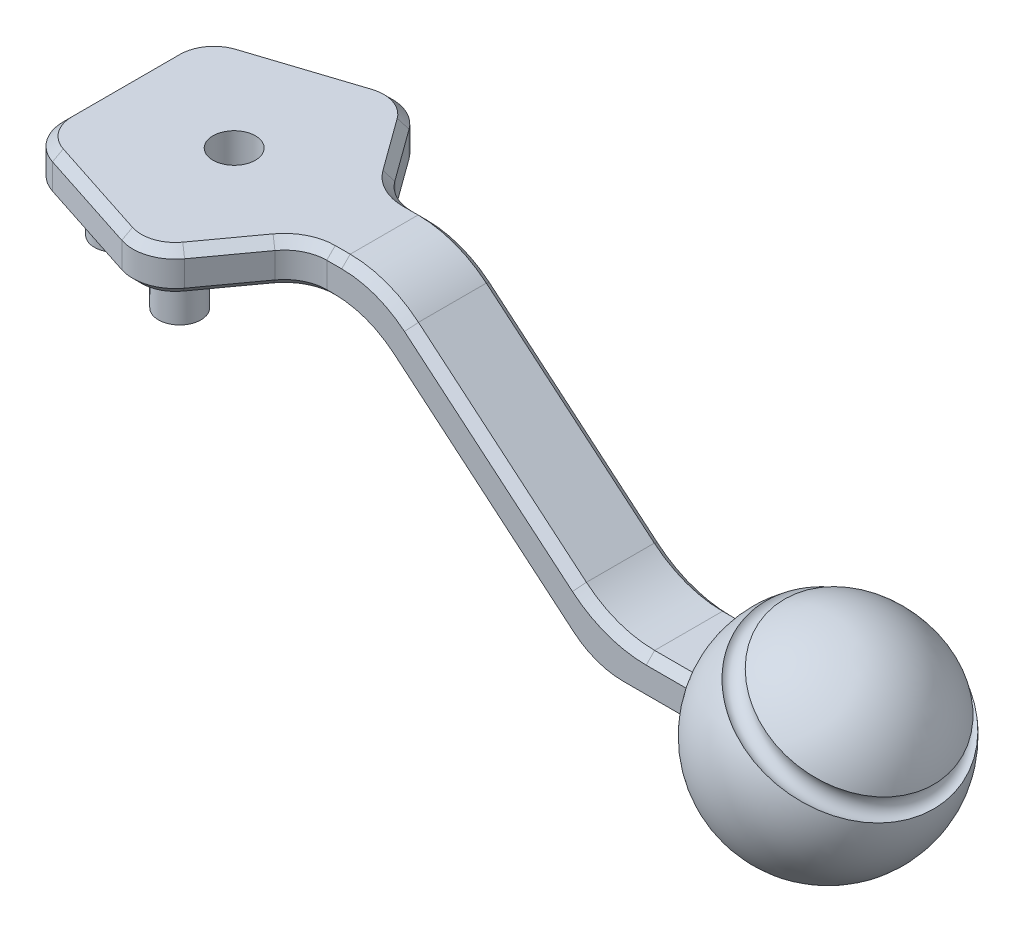
SolidWorks part; units mm, degrees
ref_plane "Front Plane" through (0, 0, 0) normal (0, 0, 1) x (1, 0, 0)
ref_plane "Top Plane" through (0, 0, 0) normal (0, 1, 0) x (1, 0, 0)
ref_plane "Right Plane" through (0, 0, 0) normal (1, 0, 0) x (0, 0, -1)
sketch "Sketch2" plane through (0, 0, 0) normal (0, 0, 1) x (1, 0, 0)
  line L0 (0, 31.75) -> (0, 0)
  line L1 (0, 0) -> (0, -31.75)
  arc A0 (0, -31.75) -> (0, 31.75) centre (0, 0) ccw
  dimension "D1" = 63.5
revolve "Revolve1" add sketch "Sketch2" angle 360 about L0
sketch "Sketch10" plane through (0, 0, 0) normal (1, 0, 0) x (0, 0, -1)
  line L1 (-12.7, 6.35) -> (12.7, 6.35)
  line L2 (-12.7, 6.35) -> (-12.7, -6.35)
  line L3 (-12.7, -6.35) -> (12.7, -6.35)
  line L4 (12.7, 6.35) -> (12.7, -6.35)
  line L5 (-12.7, 6.35) -> (12.7, -6.35) construction
  line L6 (-12.7, -6.35) -> (12.7, 6.35) construction
  point P0 (0, 0)
  dimension "D1" = 12.7
  dimension "D2" = 25.4
sketch "Sketch15" plane through (0, 0, 0) normal (0, 0, 1) x (1, 0, 0)
  line L0 (0, 0) -> (0, 6.35)
  line L1 (0, 6.35) -> (-53.34, 6.35)
  line L2 (-53.34, 6.35) -> (-121.3358, 63.5)
  line L3 (-121.3358, 63.5) -> (-190.5, 63.5)
  line L4 (-10.9985, -6.35) -> (-10.9985, -6.35)
  line L5 (-10.9985, -6.35) -> (-57.9683, -6.35)
  line L6 (-57.9683, -6.35) -> (-125.9641, 50.8)
  line L7 (-125.9641, 50.8) -> (-190.5, 50.8)
  line L8 (-10.9985, -6.35) -> (0, -6.35)
  line L9 (0, 6.35) -> (0, -6.35) construction
  line L10 (0, -6.35) -> (0, 6.35) construction
  line L11 (0, -6.35) -> (0, 0)
  line L12 (-190.5, 63.5) -> (-190.5, 50.8)
  dimension "D1" = 6.35
  dimension "D2" = 53.34
  dimension "D3" = 121.3358
  dimension "D4" = 190.5
  dimension "D5" = 63.5
  dimension "D6" = 12.7
extrude "Boss-Extrude4" add sketch "Sketch15" along normal mid plane 25.4
fillet "Fillet5" radius 31.75 2 edges at (-121.3358, 63.5, 0) (-53.34, 6.35, 0)
fillet "Fillet6" radius 25.4 2 edges at (-125.9641, 50.8, 0) (-57.9683, -6.35, 0)
sketch "Sketch19" plane through (0, 0, 0) normal (0, 1, 0) x (1, 0, 0)
  line L1 (-134.6303, 0) -> (-164.4598, 41.0568)
  line L2 (-164.4598, 41.0568) -> (-212.725, 25.3745)
  line L3 (-212.725, 25.3745) -> (-212.725, -25.3745)
  line L4 (-212.725, -25.3745) -> (-164.4598, -41.0568)
  line L5 (-164.4598, -41.0568) -> (-134.6303, 0)
  circle A0 centre (-177.8, 0) radius 34.925 construction
  point P1 (0, 0)
  point P8 (0, 0)
  dimension "D1" = 69.85
  dimension "D2" = 177.8
extrude "Boss-Extrude5" add sketch "Sketch19" against normal blind 12.7 from vertex at 63.5 starting at point (-190.5, 63.5, 12.7)
sketch "Sketch20" plane through (0, 0, 0) normal (0, 1, 0) x (1, 0, 0)
  circle A0 centre (-177.8, 0) radius 6.35
  point P2 (0, 0)
  point P4 (0, 0)
  dimension "D1" = 12.7
  dimension "D2" = 177.8
extrude "Cut-Extrude6" cut sketch "Sketch20" along normal blind 112.014
fillet "Fillet7" radius 12.7 6 edges at (-143.8574, 57.15, -12.7) (-164.4598, 57.15, -41.0568) (-212.725, 57.15, -25.3745) (-212.725, 57.15, 25.3745) (-164.4598, 57.15, 41.0568) (-143.8574, 57.15, 12.7)
chamfer "Chamfer2" distance 2.54 angle 45 42 edges at (-153.3486, 63.5, -25.7635) (-153.3486, 50.8, -25.7635) (-188.5924, 63.5, -33.2156) (-188.5924, 50.8, -33.2156) (-212.725, 63.5, 0) (-212.725, 50.8, 0) (-188.5924, 63.5, 33.2156) (-188.5924, 50.8, 33.2156) (-153.3486, 63.5, 25.7635) (-153.3486, 50.8, 25.7635) (-136.3036, 50.8, 12.7) (-126.5236, 49.2646, 12.7) (-91.9662, 22.225, 12.7) (-38.5549, -6.35, 12.7) (-57.4088, -4.8146, 12.7) (-136.3036, 50.8, -12.7) (-126.5236, 49.2646, -12.7) (-91.9662, 22.225, -12.7) (-57.4088, -4.8146, -12.7) (-38.5549, -6.35, -12.7) (-35.0837, 6.35, -12.7) (-52.6406, 8.2692, -12.7) (-135.1465, 63.5, -12.7) (-87.3379, 34.925, -12.7) (-122.0352, 61.5808, -12.7) (-35.0837, 6.35, 12.7) (-52.6406, 8.2692, 12.7) (-87.3379, 34.925, 12.7) (-135.1465, 63.5, 12.7) (-122.0352, 61.5808, 12.7) (-143.1521, 50.8, 14.0842) (-165.3863, 50.8, 38.2055) (-210.2995, 50.8, 23.6123) (-210.2995, 50.8, -23.6123) (-165.3863, 50.8, -38.2055) (-143.1521, 50.8, -14.0842) (-143.1521, 63.5, -14.0842) (-165.3863, 63.5, -38.2055) (-210.2995, 63.5, -23.6123) (-143.1521, 63.5, 14.0842) (-210.2995, 63.5, 23.6123) (-165.3863, 63.5, 38.2055)
sketch "Sketch22" plane through (0, 0, 0) normal (0, 1, 0) x (1, 0, 0)
  line L0 (-177.8, 0) -> (-169.951, 24.1568) construction
  line L1 (-177.8, 0) -> (-198.349, 14.9297) construction
  line L2 (-177.8, 0) -> (-198.349, -14.9297) construction
  line L3 (-177.8, 0) -> (-169.951, -24.1568) construction
  circle A0 centre (-177.8, 0) radius 25.4 construction
  circle A1 centre (-198.349, -14.9297) radius 6.35
  circle A2 centre (-198.349, 14.9297) radius 6.35
  circle A3 centre (-169.951, 24.1568) radius 6.35
  circle A4 centre (-169.951, -24.1568) radius 6.35
  dimension "D1" = 50.8
  dimension "D2" = 12.7
extrude "Boss-Extrude7" add sketch "Sketch22" against normal blind 12.7 from surface at 50.8 starting at face at (-184.15, 50.8, 0)
sketch "Sketch23" plane through (0, 0, 0) normal (0, 0, 1) x (1, 0, 0)
  line L0 (0, 0) -> (0, 55.3197) construction
  line L1 (0, 0) -> (27.6221, 47.8428) construction
  line L2 (0, 0) -> (-29.1875, 50.5542) construction
  circle A0 centre (-15.875, 27.4963) radius 3.175
  arc A1 (-31.1085, -6.35) -> (-31.1085, 6.35) centre (0, 0) ccw construction
  dimension "D3" = 6.35
  dimension "D1" = 30
  dimension "D2" = 30
revolve "Cut-Revolve12" cut sketch "Sketch23" angle 360 about L1
